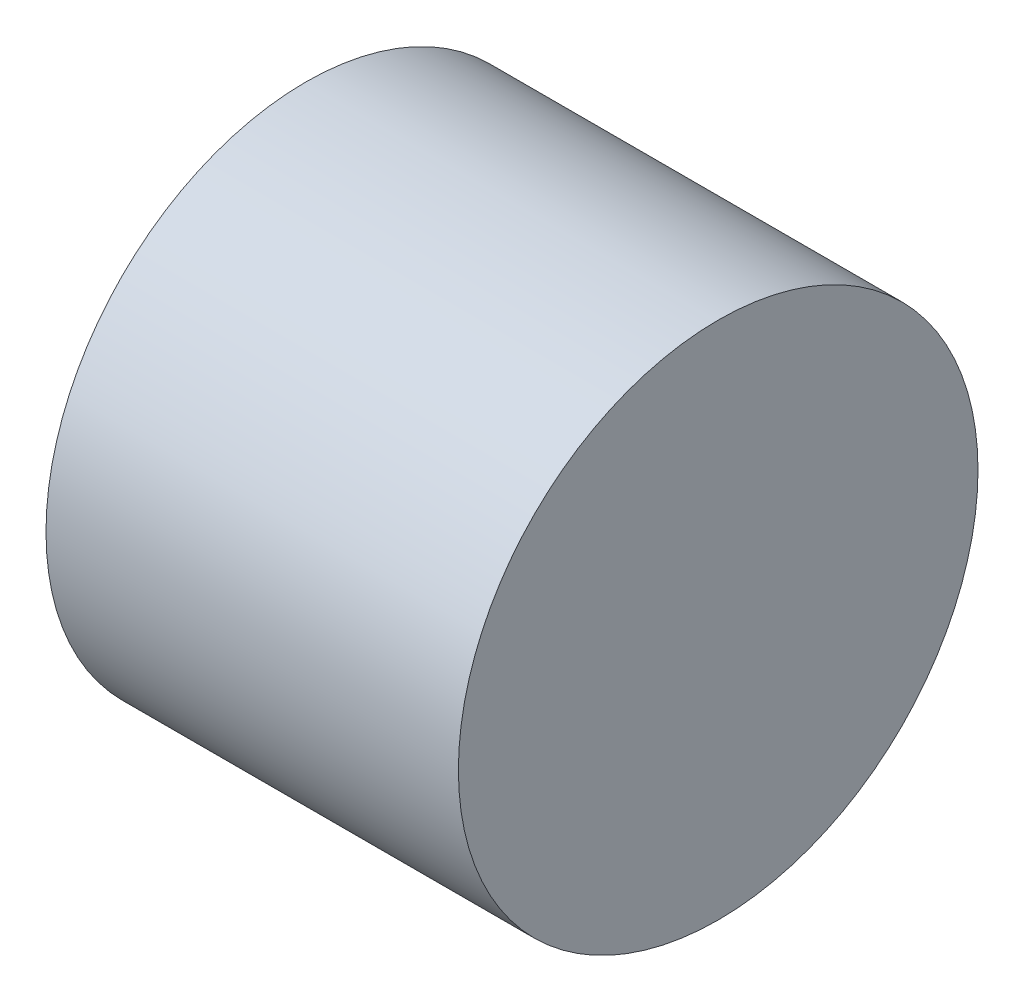
SolidWorks part; units mm, degrees
ref_plane "Front Plane" through (0, 0, 0) normal (0, 0, 1) x (1, 0, 0)
ref_plane "Top Plane" through (0, 0, 0) normal (0, 1, 0) x (1, 0, 0)
ref_plane "Right Plane" through (0, 0, 0) normal (1, 0, 0) x (0, 0, -1)
sketch "Sketch1" plane through (0, 0, 0) normal (1, 0, 0) x (0, 0, -1)
  circle A0 centre (0, 0) radius 31.5
  dimension "D1" = 63
extrude "Boss-Extrude1" add sketch "Sketch1" along normal mid plane 50
